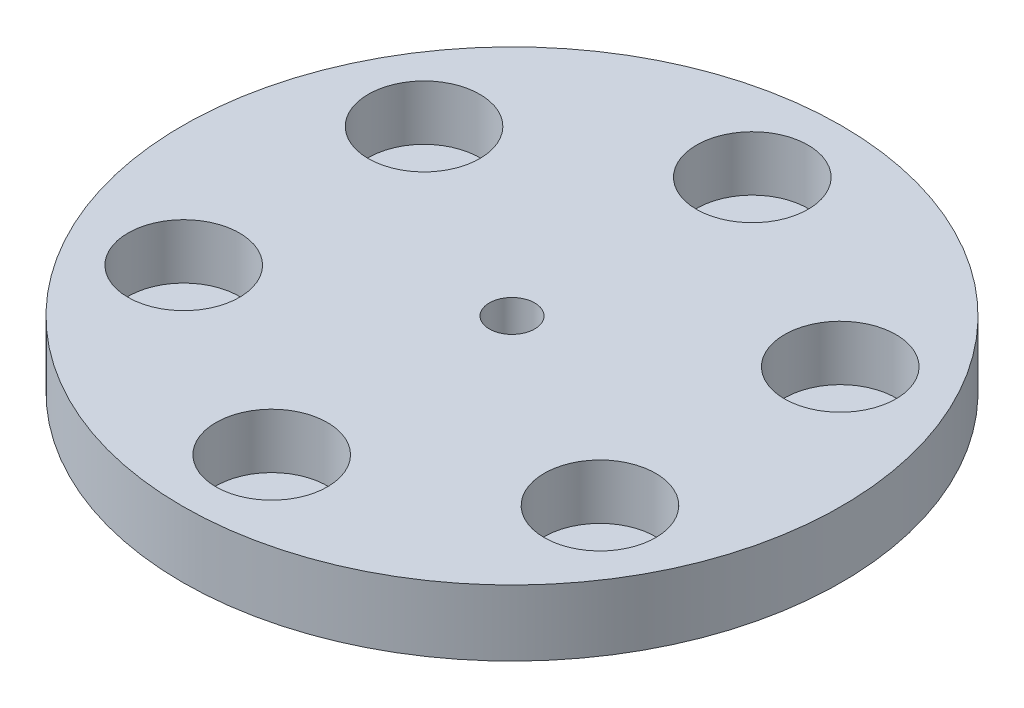
SolidWorks part; units mm, degrees
ref_plane "Plano frontal" through (0, 0, 0) normal (0, 0, 1) x (1, 0, 0)
ref_plane "Plano superior" through (0, 0, 0) normal (0, 1, 0) x (1, 0, 0)
ref_plane "Plano direito" through (0, 0, 0) normal (1, 0, 0) x (0, 0, -1)
sketch "Esboço1" plane through (0, 0, 0) normal (0, 1, 0) x (1, 0, 0)
  circle A0 centre (0, 0) radius 60
  circle A1 centre (0, 0) radius 4.125
  dimension "D1" = 120
  dimension "D2" = 8.25
extrude "Ressalto-extrusão1" add sketch "Esboço1" along normal blind 12
sketch "Esboço2" plane through (0, 12, 0) normal (0, 1, 0) x (1, 0, 0)
  circle A0 centre (0, 43.75) radius 10.15
  circle A1 centre (37.8886, 21.875) radius 10.15
  circle A2 centre (37.8886, -21.875) radius 10.15
  circle A3 centre (0, -43.75) radius 10.15
  circle A4 centre (-37.8886, -21.875) radius 10.15
  circle A5 centre (-37.8886, 21.875) radius 10.15
  point P16 (0, 0)
  dimension "D1" = 20.3
  dimension "D2" = 43.75
  dimension "D3" = 6
extrude "Corte-extrusão1" cut sketch "Esboço2" against normal blind 10
